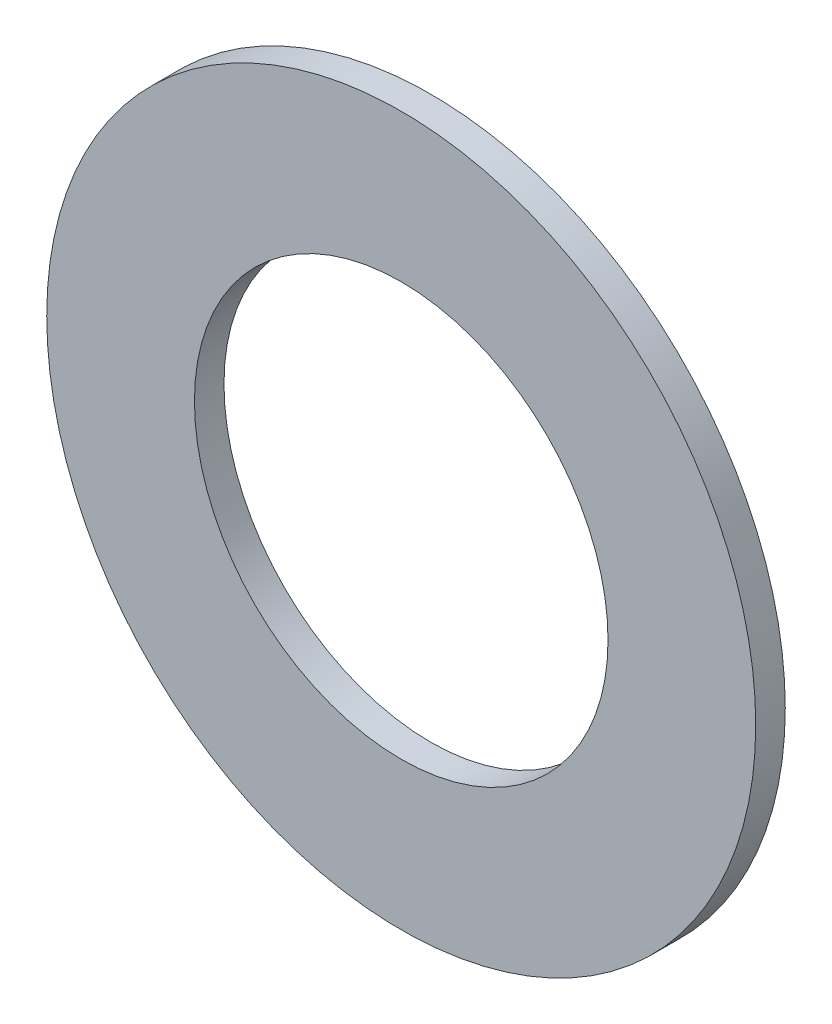
SolidWorks part; units mm, degrees
ref_plane "Front Plane" through (0, 0, 0) normal (0, 0, 1) x (1, 0, 0)
ref_plane "Top Plane" through (0, 0, 0) normal (0, 1, 0) x (1, 0, 0)
ref_plane "Right Plane" through (0, 0, 0) normal (1, 0, 0) x (0, 0, -1)
sketch "Sketch1" plane through (0, 0, 0) normal (0, 0, 1) x (1, 0, 0)
  circle A0 centre (0, 0) radius 44.45
  circle A1 centre (0, 0) radius 76.2
  dimension "D1" = 88.9
  dimension "D2" = 152.4
extrude "Boss-Extrude1" add sketch "Sketch1" along normal blind 6.35
